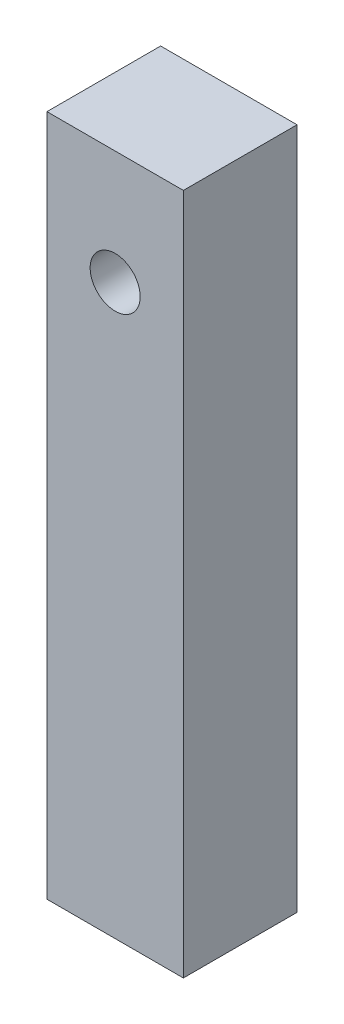
SolidWorks part; units mm, degrees
ref_plane "Front Plane" through (0, 0, 0) normal (0, 0, 1) x (1, 0, 0)
ref_plane "Top Plane" through (0, 0, 0) normal (0, 1, 0) x (1, 0, 0)
ref_plane "Right Plane" through (0, 0, 0) normal (1, 0, 0) x (0, 0, -1)
sketch "Sketch1" plane through (0, 0, 0) normal (0, 1, 0) x (1, 0, 0)
  line L0 (-2.0455, 4.4781) -> (3.9545, 4.4781)
  line L1 (3.9545, 4.4781) -> (3.9545, -0.5219)
  line L2 (3.9545, -0.5219) -> (-2.0455, -0.5219)
  line L3 (-2.0455, -0.5219) -> (-2.0455, 4.4781)
  dimension "D1" = 6
  dimension "D2" = 5
extrude "Boss-Extrude1" add sketch "Sketch1" along normal blind 30
sketch "Sketch2" plane through (0, 0, 0.5219) normal (0, 0, 1) x (1, 0, 0)
  line L0 (3.9545, 30) -> (3.9545, 0) construction
  line L1 (-2.0455, 0) -> (3.9545, 0) construction
  circle A0 centre (0.9545, 25) radius 1.1
  dimension "D1" = 2.2
  dimension "D2" = 3
  dimension "D3" = 25
extrude "Cut-Extrude1" cut sketch "Sketch2" against normal blind 20
